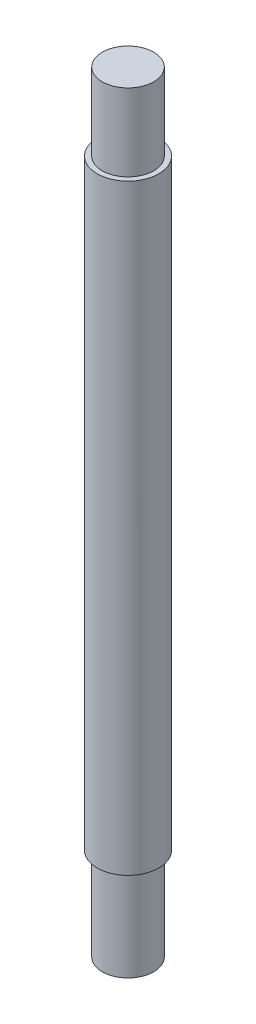
SolidWorks part; units mm, degrees
ref_plane "正面" through (0, 0, 0) normal (0, 0, 1) x (1, 0, 0)
ref_plane "平面" through (0, 0, 0) normal (0, 1, 0) x (1, 0, 0)
ref_plane "右側面" through (0, 0, 0) normal (1, 0, 0) x (0, 0, -1)
sketch "ｽｹｯﾁ1" plane through (0, 0, 0) normal (0, 1, 0) x (1, 0, 0)
  circle A0 centre (0, 0) radius 6
extrude "ﾎﾞｽ - 押し出し1" add sketch "ｽｹｯﾁ1" along normal blind 150
sketch "ｽｹｯﾁ2" plane through (0, 150, 0) normal (0, 1, 0) x (1, 0, 0)
  circle A0 centre (0, 0) radius 5
  circle A1 centre (0, 0) radius 6
extrude "ｶｯﾄ - 押し出し1" cut sketch "ｽｹｯﾁ2" against normal blind 15
sketch "ｽｹｯﾁ3" plane through (0, 0, 0) normal (0, -1, 0) x (-1, 0, 0)
  circle A0 centre (0, 0) radius 6
  circle A1 centre (0, 0) radius 5
extrude "ｶｯﾄ - 押し出し2" cut sketch "ｽｹｯﾁ3" against normal blind 18
